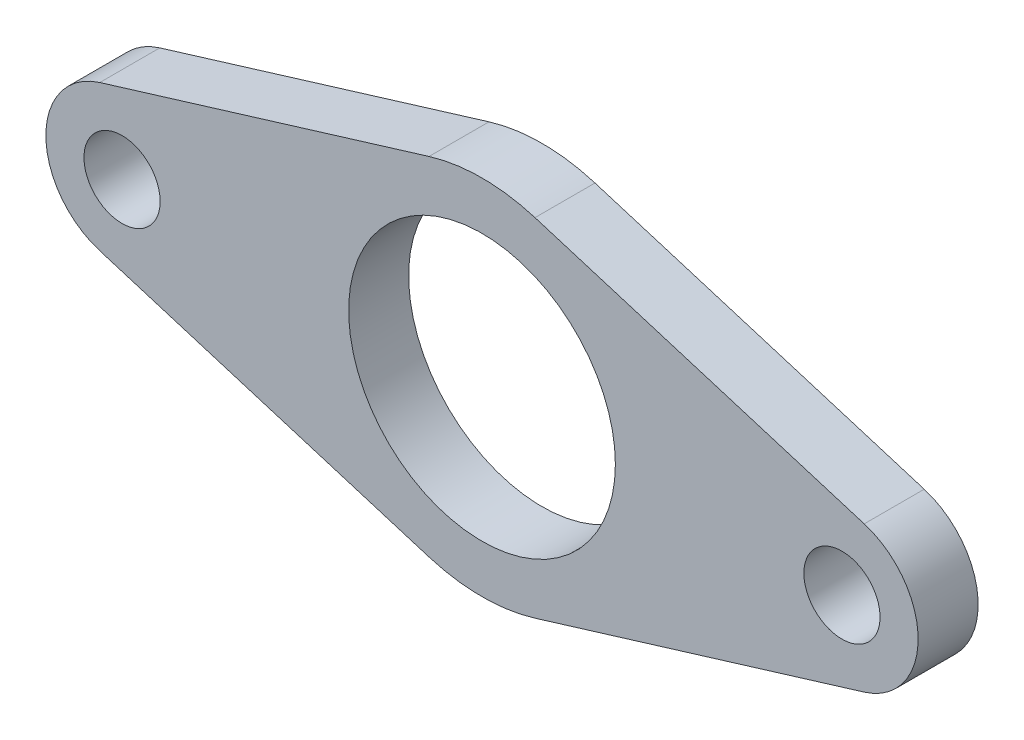
SolidWorks part; units mm, degrees
ref_plane "Alzado" through (0, 0, 0) normal (0, 0, 1) x (1, 0, 0)
ref_plane "Planta" through (0, 0, 0) normal (0, 1, 0) x (1, 0, 0)
ref_plane "Vista lateral" through (0, 0, 0) normal (1, 0, 0) x (0, 0, -1)
sketch "Croquis1" plane through (0, 0, 0) normal (0, 0, 1) x (1, 0, 0)
  line L0 (0, 15.61) -> (0, -15.6974) construction
  line L1 (-31.8553, 6.0729) -> (-4.4161, 14.4555)
  line L2 (7.8211, 0) -> (-7.4495, 0) construction
  line L3 (-31.8553, -6.0729) -> (-4.4161, -14.4555)
  line L4 (31.8553, -6.0729) -> (4.4161, -14.4555)
  line L5 (31.8553, 6.0729) -> (4.4161, 14.4555)
  circle A0 centre (0, 0) radius 11.115
  arc A1 (-4.4161, -14.4555) -> (4.4161, -14.4555) centre (0, 0) ccw
  circle A2 centre (-30, 0) radius 3.175
  arc A3 (-31.8553, 6.0729) -> (-31.8553, -6.0729) centre (-30, 0) ccw
  circle A4 centre (30, 0) radius 3.175
  arc A5 (31.8553, 6.0729) -> (31.8553, -6.0729) centre (30, 0) cw
  arc A6 (4.4161, 14.4555) -> (-4.4161, 14.4555) centre (0, 0) ccw
  dimension "D1" = 22.23
  dimension "D2" = 4
  dimension "D3" = 6.35
  dimension "D4" = 12.7
  dimension "D5" = 30
extrude "Saliente-Extruir1" add sketch "Croquis1" along normal blind 5
